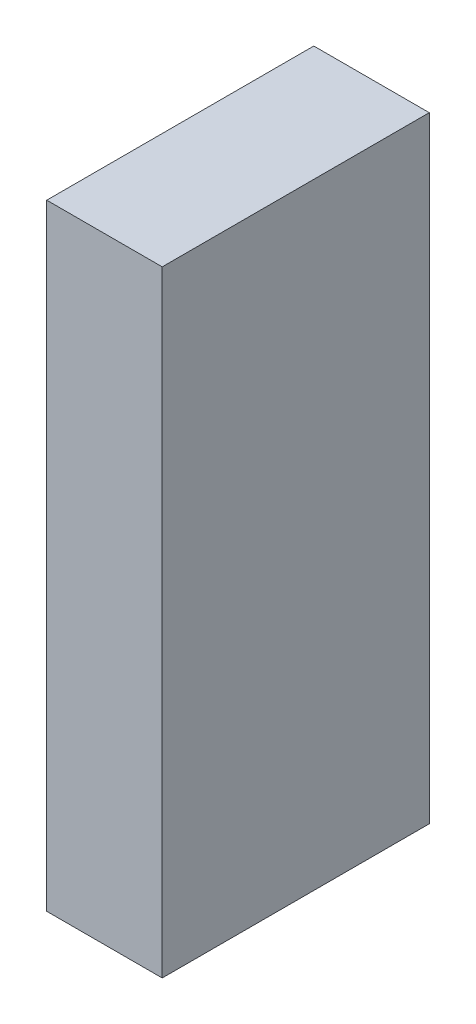
SolidWorks part; units mm, degrees
material "Pine"
ref_plane "Front Plane" through (0, 0, 0) normal (0, 0, 1) x (1, 0, 0)
ref_plane "Top Plane" through (0, 0, 0) normal (0, 1, 0) x (1, 0, 0)
ref_plane "Right Plane" through (0, 0, 0) normal (1, 0, 0) x (0, 0, -1)
sketch "Sketch1" plane through (0, 0, 0) normal (0, 1, 0) x (1, 0, 0)
  line L1 (19.05, -44.0531) -> (-19.05, -44.0531)
  line L2 (19.05, -44.0531) -> (19.05, 44.0531)
  line L3 (19.05, 44.0531) -> (-19.05, 44.0531)
  line L4 (-19.05, -44.0531) -> (-19.05, 44.0531)
  line L5 (19.05, -44.0531) -> (-19.05, 44.0531) construction
  line L6 (19.05, 44.0531) -> (-19.05, -44.0531) construction
  point P0 (0, 0)
  dimension "D1" = 38.1
  dimension "D2" = 88.1063
extrude "Boss-Extrude1" add sketch "Sketch1" along normal blind 203.2
